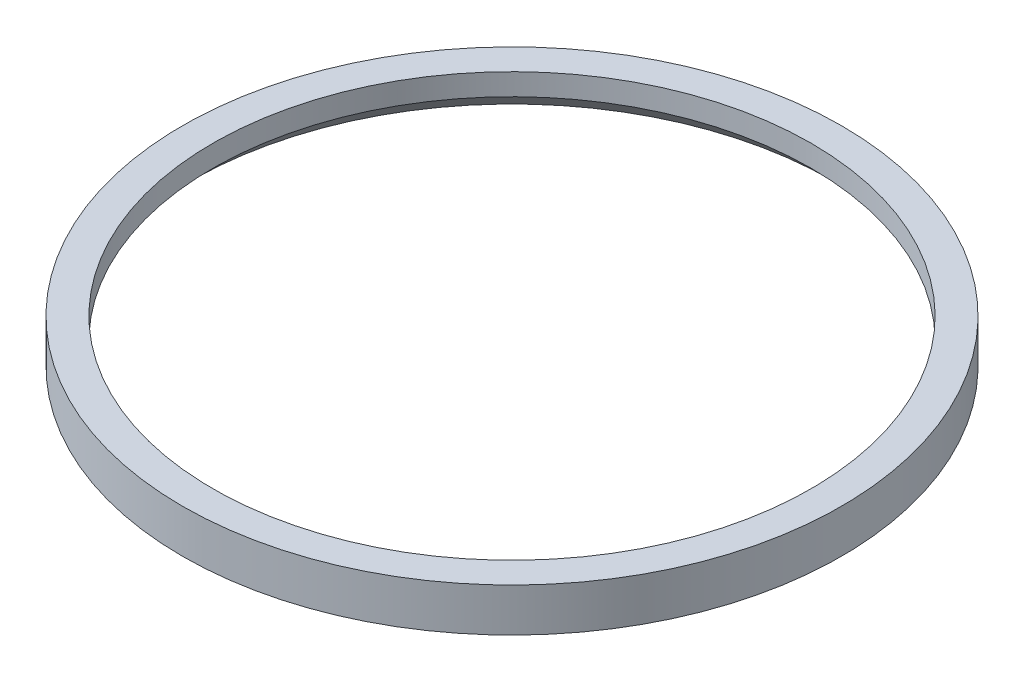
SolidWorks part; units mm, degrees
ref_plane "Plano frontal" through (0, 0, 0) normal (0, 0, 1) x (1, 0, 0)
ref_plane "Plano superior" through (0, 0, 0) normal (0, 1, 0) x (1, 0, 0)
ref_plane "Plano direito" through (0, 0, 0) normal (1, 0, 0) x (0, 0, -1)
sketch "Sketch1" plane through (0, 0, 0) normal (1, 0, 0) x (0, 0, -1)
  line L0 (0, 0) -> (0, 10.4069) construction
  line L1 (18.5, 0) -> (19, 0)
  line L2 (18.5, 0) -> (17.25, 1.25)
  line L3 (17.25, 1.25) -> (17.25, 2.5)
  line L4 (17.25, 2.5) -> (19, 2.5)
  line L5 (19, 2.5) -> (19, 0)
  dimension "D1" = 19
  dimension "D2" = 2.5
  dimension "D3" = 1.75
  dimension "D4" = 1.25
  dimension "D5" = 45
revolve "Revolve1" add sketch "Sketch1" angle 360 about L0
